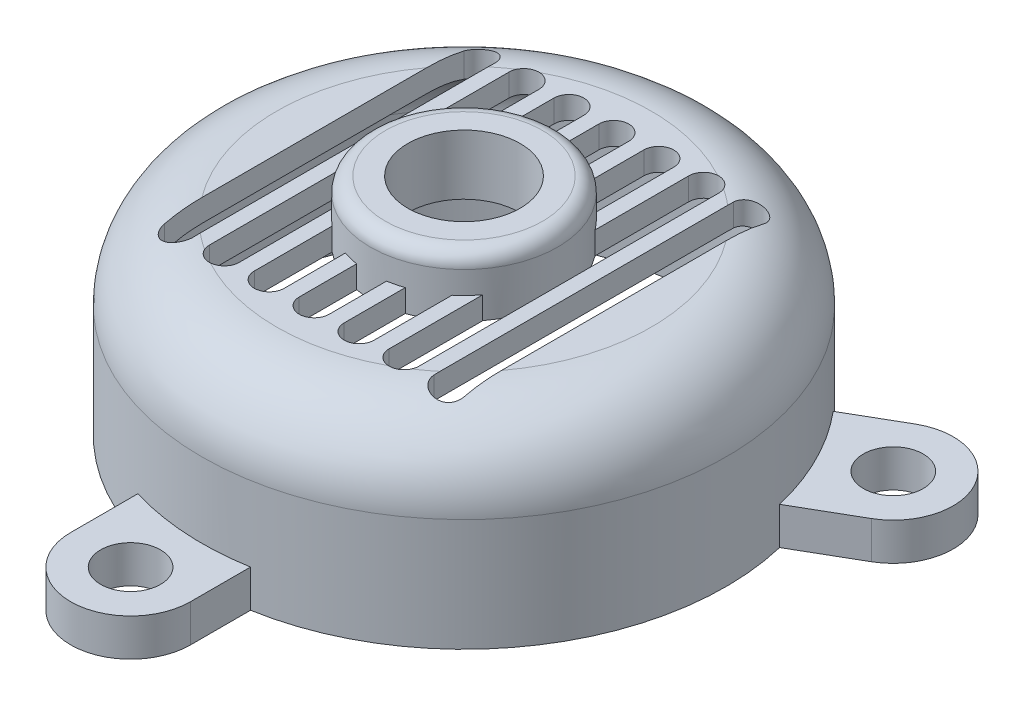
SolidWorks part; units mm, degrees
ref_plane "Front Plane" through (0, 0, 0) normal (0, 0, 1) x (1, 0, 0)
ref_plane "Top Plane" through (0, 0, 0) normal (0, 1, 0) x (1, 0, 0)
ref_plane "Right Plane" through (0, 0, 0) normal (1, 0, 0) x (0, 0, -1)
sketch "Sketch1" plane through (0, 0, 0) normal (0, 1, 0) x (1, 0, 0)
  circle A0 centre (0, 0) radius 35
  dimension "D1" = 70
extrude "Boss-Extrude1" add sketch "Sketch1" along normal blind 25
fillet "Fillet1" radius 10 1 edges at (0, 25, 35)
shell "Shell1" thickness 3
sketch "Sketch2" plane through (0, 0, 0) normal (0, -1, 0) x (1, 0, 0)
  line L1 (-10.0196, 42.5) -> (5.9804, 42.5) construction
  line L2 (-10.0196, 42.5) -> (-10.0196, 32)
  line L3 (-10.0196, 32) -> (5.9804, 32)
  line L4 (5.9804, 42.5) -> (5.9804, 32)
  line L5 (-10.0196, 42.5) -> (5.9804, 32) construction
  line L6 (-10.0196, 32) -> (5.9804, 42.5) construction
  arc A0 (5.9804, 42.5) -> (-10.0196, 42.5) centre (-2.0196, 42.5) ccw
  circle A1 centre (-2.0196, 42.5) radius 4
  circle A2 centre (0, 0) radius 32 construction
  point P0 (-2.0196, 37.25)
  dimension "D1" = 8
  dimension "D2" = 16
  dimension "D3" = 42.5
extrude "Boss-Extrude2" add sketch "Sketch2" against normal blind 5
pattern_circular "CirPattern1" count 3 over 360 about axis through (0, 0, 0) along (0, 1, 0) of "Boss-Extrude2"
sketch "Sketch3" plane through (0, 25, 0) normal (0, 1, 0) x (1, 0, 0)
  line L0 (-18, 20) -> (-18, -20) construction
  line L1 (-16, 20) -> (-16, -20)
  line L2 (-20, 20) -> (-20, -20)
  arc A0 (-16, 20) -> (-20, 20) centre (-18, 20) ccw
  arc A1 (-20, -20) -> (-16, -20) centre (-18, -20) ccw
  point P2 (-18, 0)
  dimension "D1" = 2
  dimension "D2" = 40
  dimension "D3" = 18
extrude "Cut-Extrude2" cut sketch "Sketch3" against normal blind 5 contours L2 A1 L1 A0
sketch "Sketch5" plane through (0, 25, 0) normal (0, 1, 0) x (1, 0, 0)
  line L0 (0, 0) -> (11.7812, 0)
sketch "Sketch7" plane through (0, 25, 0) normal (0, 1, 0) x (1, 0, 0)
  line L0 (0, 0) -> (13.5087, 0)
pattern_linear "LPattern2" count 7 spacing 6 along (1, 0, 0) of "Cut-Extrude2"
sketch "Sketch8" plane through (0, 25, 0) normal (0, 1, 0) x (1, 0, 0)
  circle A0 centre (0, 0) radius 12.5
  dimension "D1" = 25
extrude "Boss-Extrude3" add sketch "Sketch8" along normal blind 5 and the other way blind 3
fillet "Fillet2" radius 2 1 edges at (0, 30, 12.5)
sketch "Sketch9" plane through (0, 30, 0) normal (0, 1, 0) x (1, 0, 0)
  circle A0 centre (0, 0) radius 7.5
  dimension "D1" = 15
extrude "Cut-Extrude3" cut sketch "Sketch9" against normal through all
